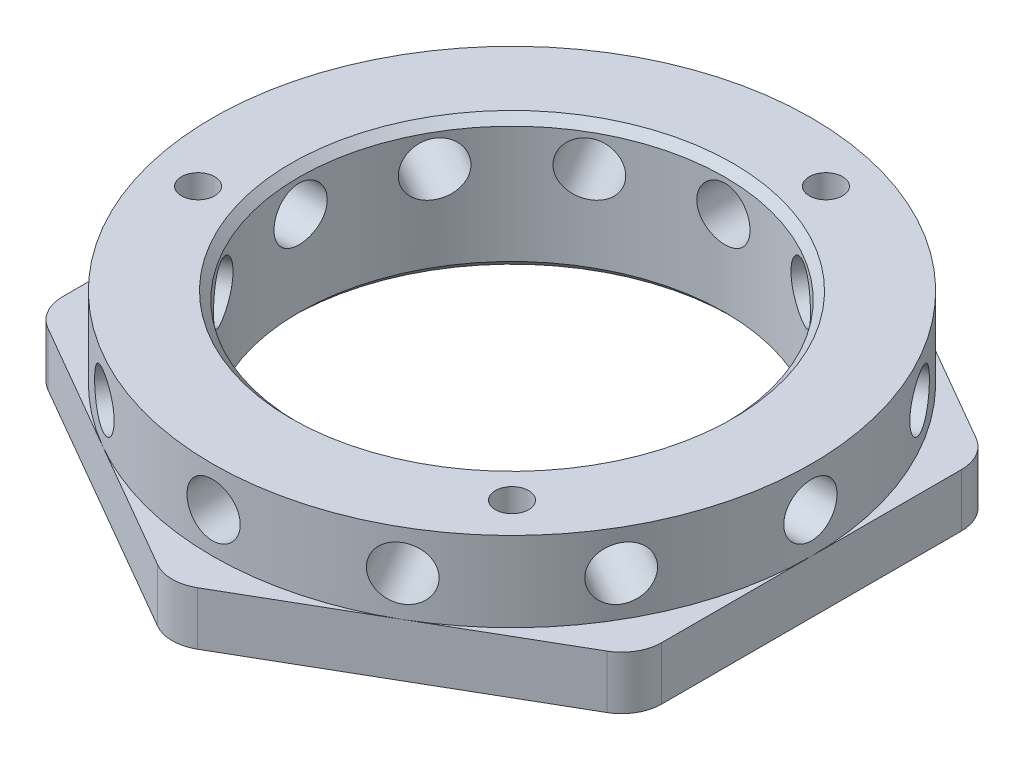
SolidWorks part; units mm, degrees
material "3.3547 (EN-AW 5083)"
ref_plane "Front Plane" through (0, 0, 0) normal (0, 0, 1) x (1, 0, 0)
ref_plane "Top Plane" through (0, 0, 0) normal (0, 1, 0) x (1, 0, 0)
ref_plane "Right Plane" through (0, 0, 0) normal (1, 0, 0) x (0, 0, -1)
sketch "Sketch1" plane through (0, 0, 0) normal (0, 1, 0) x (1, 0, 0)
  circle A1 centre (0, 0) radius 16 construction
  circle A3 centre (0, 0) radius 16
  circle A15 centre (0, 0) radius 22.5
  dimension "D1" = 6.5
extrude "Boss-Extrude1" add sketch "Sketch1" against normal blind 6
sketch "Sketch2" plane through (0, -6, 0) normal (0, -1, 0) x (1, 0, 0)
  line L1 (22.5, -11.2583) -> (22.5, 11.2583)
  line L2 (21, 13.8564) -> (1.5, 25.1147)
  line L3 (-1.5, 25.1147) -> (-21, 13.8564)
  line L4 (-22.5, 11.2583) -> (-22.5, -11.2583)
  line L5 (-21, -13.8564) -> (-1.5, -25.1147)
  line L6 (1.5, -25.1147) -> (21, -13.8564)
  circle A0 centre (0, 0) radius 22.5 construction
  arc A1 (-22.5, -11.2583) -> (-21, -13.8564) centre (-19.5, -11.2583) ccw
  arc A2 (-1.5, -25.1147) -> (1.5, -25.1147) centre (0, -22.5167) ccw
  arc A3 (22.5, -11.2583) -> (21, -13.8564) centre (19.5, -11.2583) cw
  arc A4 (22.5, 11.2583) -> (21, 13.8564) centre (19.5, 11.2583) ccw
  arc A5 (1.5, 25.1147) -> (-1.5, 25.1147) centre (0, 22.5167) ccw
  arc A6 (-21, 13.8564) -> (-22.5, 11.2583) centre (-19.5, 11.2583) ccw
  circle A7 centre (0, 0) radius 16 construction
  circle A8 centre (0, 0) radius 16
  point P22 (0, 25.9808)
  dimension "D2" = 3
  dimension "D1" = 45
extrude "Boss-Extrude2" add sketch "Sketch2" along normal blind 4
hole_wizard "Ø4.0mm Dowel Hole1" positions "3DSketch1" profile "Sketch4" hole size "Ø4.0" standard "DIN"
sketch3d "3DSketch1"
  line L0 (0, 0, 0) -> (22.5, 0, 0) construction
  line L1 (22.5, 0, 0) -> (22.5, -6, 0) construction
  circle A0 centre (0, 0, 0) radius 22.5 construction
  circle A1 centre (0, -6, 0) radius 22.5 construction
  point P0 (22.5, -3, 0)
  point P8 (0, 22.5, 0)
  point P12 (0, 16.5, 0)
  point P15 (22.5, -3, 0)
sketch "Sketch4" plane through (22.5, -3, 0) normal (0, 1, 0) x (0, 0, -1)
  line L0 (0, 0) -> (0, 6.5)
  line L1 (0, 6.5) -> (2, 6.5)
  line L2 (2, 6.5) -> (2, 0)
  line L5 (2, 0) -> (0, 0)
  line L11 (0, -6.35) -> (0, 107.95) construction
  dimension "Thru Hole Dia." = 4
  dimension "Thru Hole Depth" = 6.5
pattern_circular "CirPattern1" count 12 over 360 about axis through (0, -6, 0) along (0, 1, 0) of "Ø4.0mm Dowel Hole1"
sketch "Sketch8" plane through (0, 0, 0) normal (0, -1, 0) x (-1, 0, 0)
  line L0 (-5.8234, 21.7333) -> (-4.1411, 15.4548) construction
  line L1 (0, 0) -> (-4.1411, 15.4548) construction
  line L3 (0, 22.5) -> (-11.25, 19.4856) construction
  line L4 (0, 0) -> (-4.9823, 18.5941) construction
  line L5 (0, 0) -> (18.5941, -4.9823) construction
  circle A0 centre (0, 0) radius 16 construction
  circle A1 centre (0, 0) radius 22.5 construction
  circle A2 centre (0, 0) radius 16 construction
  circle A3 centre (0, 0) radius 22.5 construction
  arc A4 (12.9375, 18.4084) -> (9.4734, 20.4084) centre (0, 0) ccw construction
  arc A5 (2, 22.4109) -> (-2, 22.4109) centre (0, 0) ccw construction
  arc A6 (12.9375, 18.4084) -> (9.4734, 20.4084) centre (0, 0) ccw construction
  arc A7 (2, 22.4109) -> (-2, 22.4109) centre (0, 0) ccw construction
  arc A8 (-9.4734, 20.4084) -> (-12.9375, 18.4084) centre (0, 0) ccw construction
  arc A9 (-9.4734, 20.4084) -> (-12.9375, 18.4084) centre (0, 0) ccw construction
  point P11 (-4.9823, 18.5941)
  point P36 (-5.625, 20.9928)
  point P43 (18.5941, -4.9823)
  point P44 (-13.6118, -13.6118)
  dimension "D1" = 3
  dimension "D2" = 120
hole_wizard "M3 Tapped Hole2" positions "Sketch8" profile "Sketch7" tap size "M3" standard "DIN" end condition up to next
sketch "Sketch7" plane through (13.6118, 0, 13.6118) normal (1, 0, 0) x (0, 0, 1)
  line L0 (0, 0) -> (0, 10)
  line L1 (0, 10) -> (1.25, 10)
  line L2 (1.25, 10) -> (1.25, 0)
  line L5 (1.25, 0) -> (0, 0)
  line L11 (0, -6.35) -> (0, 107.95) construction
  dimension "Thru Tap Drill Dia." = 2.5
  dimension "Thru Tap Drill Depth" = 10
cosmetic thread "Hole Thread1" parameters "D2"=3
cosmetic thread "Hole Thread2" parameters "D2"=3
cosmetic thread "Hole Thread3" parameters "D2"=3
chamfer "Chamfer1" distance 0.6 angle 45 2 edges at (0, -10, -16) (0, 0, 16)
